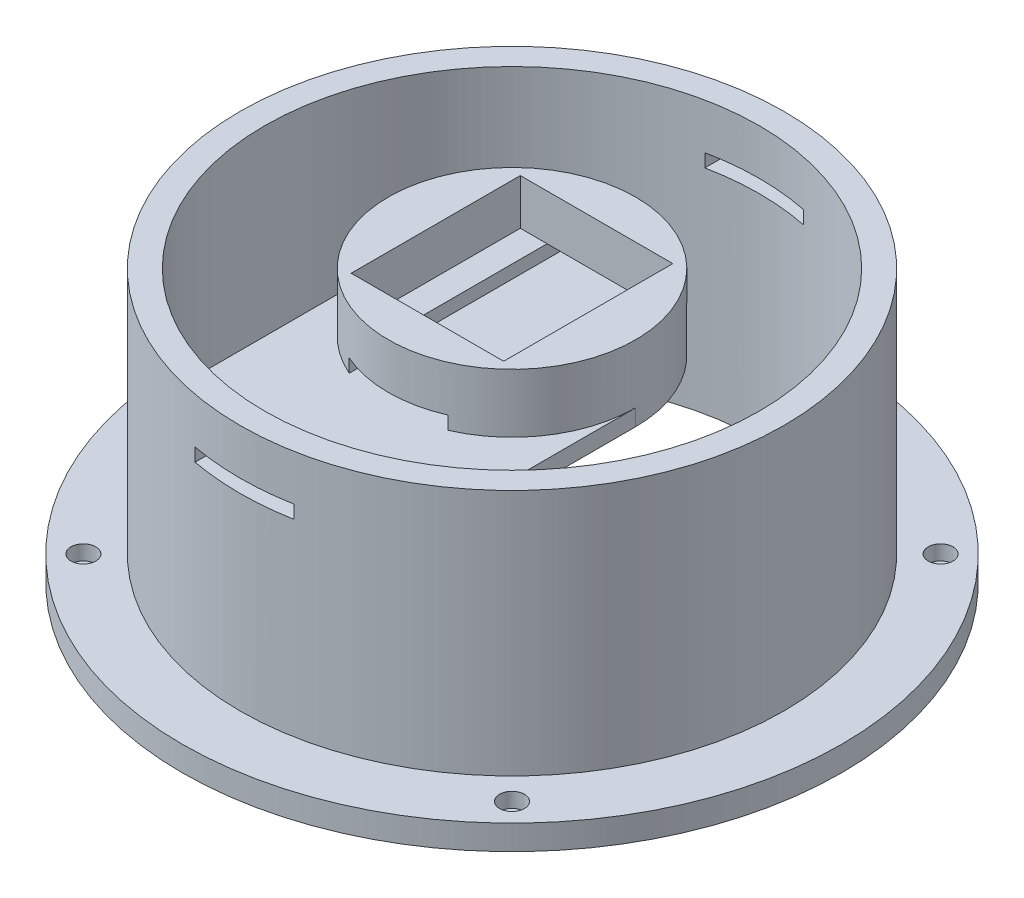
SolidWorks part; units mm, degrees
ref_plane "前视基准面" through (0, 0, 0) normal (0, 0, 1) x (1, 0, 0)
ref_plane "上视基准面" through (0, 0, 0) normal (0, 1, 0) x (1, 0, 0)
ref_plane "右视基准面" through (0, 0, 0) normal (1, 0, 0) x (0, 0, -1)
other "Configuration Table"
sketch "草图1" plane through (0, 0, 0) normal (0, 1, 0) x (1, 0, 0)
  circle A0 centre (0, 0) radius 200
  circle A1 centre (0, 0) radius 150
extrude "凸台-拉伸1" add sketch "草图1" along normal blind 15
sketch "草图2" plane through (0, 15, 0) normal (0, 1, 0) x (1, 0, 0)
  circle A0 centre (0, 0) radius 165
  circle A1 centre (0, 0) radius 150 construction
  circle A2 centre (0, 0) radius 150
extrude "凸台-拉伸2" add sketch "草图2" along normal blind 150
sketch "草图3" plane through (0, 15, 0) normal (0, 1, 0) x (1, 0, 0)
  line L1 (-130, -130) -> (130, -130)
  line L2 (-130, -130) -> (-130, 130)
  line L3 (-130, 130) -> (130, 130)
  line L4 (130, -130) -> (130, 130)
  line L5 (-130, -130) -> (130, 130) construction
  line L6 (-130, 130) -> (130, -130) construction
  point P0 (0, 0)
  dimension "D1" = 260
  dimension "D2" = 260
sketch "草图4" plane through (0, 15, 0) normal (0, 1, 0) x (1, 0, 0)
sketch "草图6" plane through (0, 15, 0) normal (0, 1, 0) x (1, 0, 0)
  point P0 (-130, 130)
  point P3 (130, 130)
  point P6 (130, -130)
  point P9 (-130, -130)
hole_wizard "M8 六角圆柱头螺钉的柱形沉头孔1" positions "草图6" profile "草图5" counterbore size "M8" standard "GB" end condition through all
sketch "草图5" plane through (-130, 15, -130) normal (1, 0, 0) x (0, 0, 1)
  line L0 (0, 0) -> (0, 15)
  line L1 (0, 15) -> (4.2, 15)
  line L3 (4.2, 15) -> (4.2, 9)
  line L4 (7.5, 9) -> (4.2, 9)
  line L5 (7.5, 9) -> (7.5, 0.025)
  line L6 (7.5, 0.025) -> (7.525, 0)
  line L7 (7.525, 0) -> (0, 0)
  line L8 (-7.5, 0.025) -> (-7.525, 0) construction
  line L11 (0, -6.35) -> (0, 107.95) construction
  dimension "通孔孔直径" = 8.4
  dimension "通孔孔深度" = 15
  dimension "柱形沉头孔直径" = 15
  dimension "柱形沉头孔深度" = 9
  dimension "近端锥形沉头孔直径" = 15.05
  dimension "近端锥形沉头孔角度" = 90
sketch "草图8" plane through (0, 0, 0) normal (0, -1, 0) x (1, 0, 0)
  circle A0 centre (0, 0) radius 75
extrude "凸台-拉伸5" add sketch "草图8" against normal blind 165 separate body contours A0
sketch "草图11" plane through (0, 165, 0) normal (0, 1, 0) x (1, 0, 0)
  line L1 (-46.25, -51.3083) -> (46.25, -51.3083)
  line L2 (-46.25, -51.3083) -> (-46.25, 51.3083)
  line L3 (-46.25, 51.3083) -> (46.25, 51.3083)
  line L4 (46.25, -51.3083) -> (46.25, 51.3083)
  line L5 (-46.25, -51.3083) -> (46.25, 51.3083) construction
  line L6 (-46.25, 51.3083) -> (46.25, -51.3083) construction
  point P0 (0, 0)
  point P6 (0, 0)
  point P7 (25.5477, -51.3083)
  dimension "D1" = 92.5
extrude "切除-拉伸3" cut sketch "草图11" against normal blind 27.7
sketch "草图12" plane through (0, 137.3, 0) normal (0, 1, 0) x (1, 0, 0)
  line L0 (46.25, 51.3083) -> (-46.25, 51.3083) construction
  line L1 (-30, -51.3083) -> (30, -51.3083)
  line L2 (-30, -51.3083) -> (-30, 51.3083)
  line L3 (-30, 51.3083) -> (30, 51.3083)
  line L4 (30, -51.3083) -> (30, 51.3083)
  line L5 (-30, -51.3083) -> (30, 51.3083) construction
  line L6 (-30, 51.3083) -> (30, -51.3083) construction
  point P0 (0, 0)
  dimension "D1" = 60
extrude "切除-拉伸6" cut sketch "草图12" against normal blind 8
sketch "草图14" plane through (0, 0, -51.3083) normal (0, 0, 1) x (1, 0, 0)
  line L0 (0, 0) -> (0, 203.7316) construction
  line L2 (-30, 137.3) -> (30, 137.3)
  line L3 (-30, 137.3) -> (-30, 129.3)
  line L4 (-30, 129.3) -> (30, 129.3)
  line L5 (30, 137.3) -> (30, 129.3)
extrude "切除-拉伸7" cut sketch "草图14" against normal blind 165 and the other way blind 220
sketch "草图15" plane through (0, 0, 0) normal (0, -1, 0) x (1, 0, 0)
  line L0 (-130, -130) -> (130, 130) construction
  circle A0 centre (0, 0) radius 75
extrude "切除-拉伸8" cut sketch "草图15" against normal blind 119.3
sketch "草图16" plane through (0, 119.3, 0) normal (0, -1, 0) x (1, 0, 0)
  line L0 (-75, 0) -> (-75, 130)
  line L2 (75, 0) -> (75, 129.9038)
  line L3 (-130, 130) -> (130, 130) construction
  circle A0 centre (0, 0) radius 75 construction
  circle A1 centre (0, 0) radius 150 construction
  circle A2 centre (0, 0) radius 75
  circle A3 centre (0, 0) radius 150
  circle M1 centre (0, 0) radius 75
extrude "凸台-拉伸6" add sketch "草图16" against normal blind 10 contours L2 A3 L0 M1
